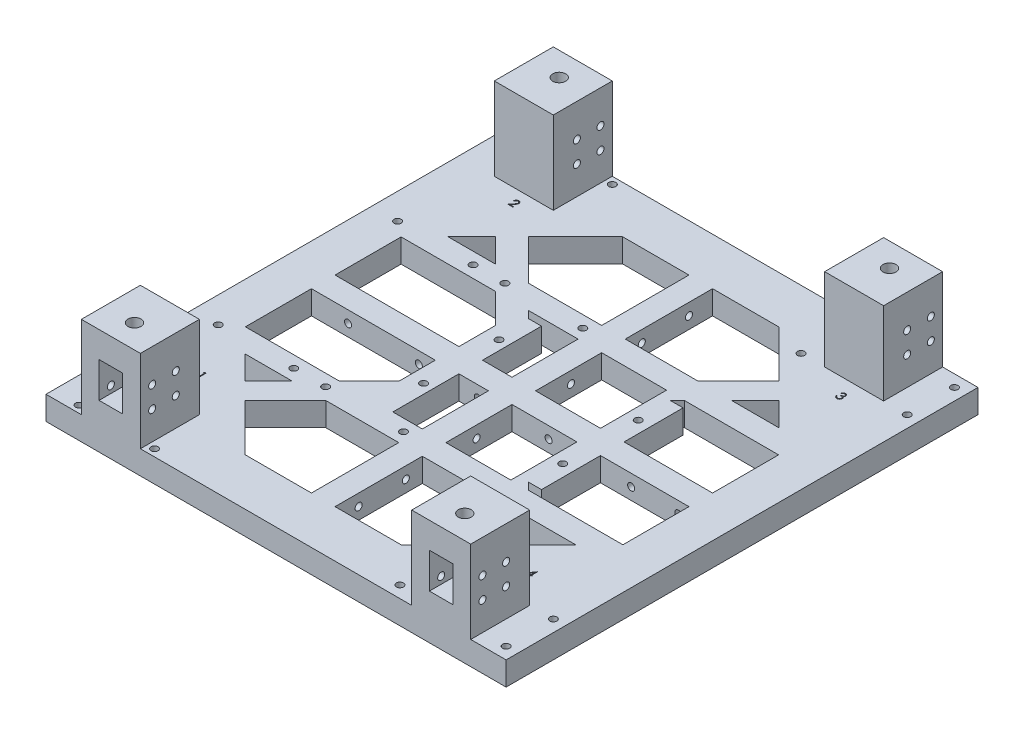
SolidWorks part; units mm, degrees
ref_plane "前视基准面" through (0, 0, 0) normal (0, 0, 1) x (1, 0, 0)
ref_plane "上视基准面" through (0, 0, 0) normal (0, 1, 0) x (1, 0, 0)
ref_plane "右视基准面" through (0, 0, 0) normal (1, 0, 0) x (0, 0, -1)
sketch "草图1" plane through (0, 0, 0) normal (0, 1, 0) x (1, 0, 0)
  line L1 (-97.5, -100) -> (97.5, -100)
  line L2 (-97.5, -100) -> (-97.5, 100)
  line L3 (-97.5, 100) -> (97.5, 100)
  line L4 (97.5, -100) -> (97.5, 100)
  line L5 (-97.5, -100) -> (97.5, 100) construction
  line L6 (-97.5, 100) -> (97.5, -100) construction
  point P0 (0, 0)
  dimension "D1" = 195
  dimension "D2" = 200
extrude "凸台-拉伸1" add sketch "草图1" along normal blind 10
sketch "草图2" plane through (0, 10, 0) normal (0, 1, 0) x (1, 0, 0)
  line L1 (-82.5, -100) -> (-57.5, -100)
  line L2 (-82.5, -100) -> (-82.5, -75)
  line L3 (-82.5, -75) -> (-57.5, -75)
  line L4 (-57.5, -100) -> (-57.5, -75)
  line L6 (-82.5, 100) -> (-57.5, 100)
  line L7 (-82.5, 100) -> (-82.5, 75)
  line L8 (-82.5, 75) -> (-57.5, 75)
  line L9 (-57.5, 100) -> (-57.5, 75)
  line L10 (82.5, 100) -> (57.5, 100)
  line L11 (82.5, 100) -> (82.5, 75)
  line L12 (82.5, 75) -> (57.5, 75)
  line L13 (57.5, 100) -> (57.5, 75)
  line L14 (97.5, 100) -> (-97.5, 100) construction
  line L15 (82.5, -75) -> (57.5, -75)
  line L16 (82.5, -75) -> (82.5, -100)
  line L17 (82.5, -100) -> (57.5, -100)
  line L18 (57.5, -75) -> (57.5, -100)
  line L19 (-97.5, -100) -> (97.5, -100) construction
  line L22 (97.5, -100) -> (97.5, 100) construction
  line L23 (-97.5, 100) -> (-97.5, -100) construction
  dimension "D1" = 0
  dimension "D2" = 0
  dimension "D3" = 0
  dimension "D4" = 0
  dimension "D5" = 40
  dimension "D6" = 25
  dimension "D7" = 40
  dimension "D8" = 25
  dimension "D9" = 25
  dimension "D10" = 25
  dimension "D11" = 25
  dimension "D12" = 25
  dimension "D13" = 40
  dimension "D14" = 25
  dimension "D15" = 40
  dimension "D16" = 25
extrude "凸台-拉伸2" add sketch "草图2" along normal blind 35
sketch "草图3" plane through (0, 0, 100) normal (0, 0, 1) x (1, 0, 0)
  line L0 (57.5, 45) -> (82.5, 45) construction
  line L1 (65, 19) -> (75, 19)
  line L2 (65, 19) -> (65, 34)
  line L3 (65, 34) -> (75, 34)
  line L4 (75, 19) -> (75, 34)
  line L5 (82.5, 45) -> (82.5, 10) construction
  dimension "D1" = 10
  dimension "D2" = 11
  dimension "D3" = 7.5
  dimension "D4" = 15
extrude "切除-拉伸1" cut sketch "草图3" against normal blind 20
sketch "草图4" plane through (0, 0, 0) normal (1, 0, 0) x (0, 0, -1)
  line L0 (0, 44.1564) -> (0, 0) construction
mirror "镜向1" about plane through (0, 0, 0) normal (1, 0, 0) of "切除-拉伸1"
mirror "镜向2" about plane through (0, 0, 0) normal (0, 0, 1) of "镜向1", "切除-拉伸1"
sketch "草图6" plane through (65, 0, 0) normal (1, 0, 0) x (0, 0, -1)
  line L0 (-80, 34) -> (-80, 19) construction
  line L1 (-95, 22) -> (-85, 22)
  line L2 (-95, 22) -> (-95, 31)
  line L3 (-95, 31) -> (-85, 31)
  line L4 (-85, 22) -> (-85, 31)
  line L5 (-80, 34) -> (-100, 34) construction
  line L6 (-80, 19) -> (-100, 19) construction
  circle A0 centre (-85, 31) radius 1.5
  circle A1 centre (-85, 22) radius 1.5
  circle A2 centre (-95, 22) radius 1.5
  circle A3 centre (-95, 31) radius 1.5
  dimension "D5" = 3
  dimension "D6" = 3
  dimension "D7" = 3
  dimension "D8" = 3
  dimension "D1" = 5
  dimension "D2" = 3
  dimension "D3" = 3
  dimension "D4" = 10
extrude "切除-拉伸2" cut sketch "草图6" against normal through all and the other way through all contours L3 A3 L2 | L2 A3 L3 | L3 A0 L4 | L4 A0 L3 | L1 A1 L4 | L2 A2 L1 | L1 A2 L2 | L4 A1 L1
mirror "镜向3" about plane through (0, 0, 0) normal (0, 0, 1) of "切除-拉伸2"
sketch "草图7" plane through (0, 0, 0) normal (0, -1, 0) x (1, 0, 0)
  line L0 (97.5, 100) -> (97.5, -100) construction
  line L1 (97.5, -100) -> (-97.5, -100) construction
  circle A0 centre (92.5, -75) radius 1.5
  circle A1 centre (92.5, -95) radius 1.5
  circle A2 centre (47.5, -75) radius 1.5
  circle A3 centre (47.5, -95) radius 1.5
  dimension "D1" = 3
  dimension "D2" = 3
  dimension "D3" = 3
  dimension "D4" = 3
  dimension "D5" = 5
  dimension "D6" = 5
  dimension "D7" = 5
  dimension "D8" = 5
  dimension "D9" = 20
  dimension "D10" = 45
  dimension "D11" = 45
  dimension "20" = 20
extrude "切除-拉伸3" cut sketch "草图7" against normal through all
mirror "镜向4" about plane through (0, 0, 0) normal (0, 0, 1) of "切除-拉伸3"
sketch "草图9" plane through (0, 45, 0) normal (0, 1, 0) x (1, 0, 0)
  line L0 (-82.5, 100) -> (-82.5, 75) construction
  line L1 (-57.5, 100) -> (-82.5, 100) construction
  circle A0 centre (-70, 90) radius 1.5
  dimension "D1" = 3
  dimension "D2" = 12.5
  dimension "D3" = 10
extrude "切除-拉伸4" cut sketch "草图9" against normal through all
sketch "草图10" plane through (0, 45, 0) normal (0, 1, 0) x (1, 0, 0)
  circle A0 centre (-70, 90) radius 2.75
  dimension "D1" = 5.5
extrude "切除-拉伸5" cut sketch "草图10" against normal blind 4
sketch "草图11" plane through (0, 0, 0) normal (0, -1, 0) x (-1, 0, 0)
  line L1 (70, 86.8246) -> (72.75, 88.4123)
  line L2 (72.75, 88.4123) -> (72.75, 91.5877)
  line L3 (72.75, 91.5877) -> (70, 93.1754)
  line L4 (70, 93.1754) -> (67.25, 91.5877)
  line L5 (67.25, 91.5877) -> (67.25, 88.4123)
  line L6 (67.25, 88.4123) -> (70, 86.8246)
  circle A0 centre (70, 90) radius 2.75 construction
  dimension "D1" = 5.5
extrude "切除-拉伸6" cut sketch "草图11" against normal blind 8
sketch "草图13" plane through (0, 0, 0) normal (0, -1, 0) x (-1, 0, 0)
  line L0 (-97.5, 100) -> (97.5, 100) construction
  line L1 (86.5, 38) -> (54.5, 38)
  line L2 (86.5, 38) -> (86.5, 97)
  line L3 (86.5, 97) -> (54.5, 97)
  line L4 (54.5, 38) -> (54.5, 97)
  line L5 (97.5, 100) -> (97.5, -100) construction
  circle A0 centre (86.5, 38) radius 1.5
  circle A1 centre (54.5, 38) radius 1.5
  circle A2 centre (54.5, 97) radius 1.5
  circle A3 centre (86.5, 97) radius 1.5
  dimension "D4" = 3
  dimension "D5" = 3
  dimension "D6" = 3
  dimension "D7" = 3
  dimension "D1" = 3
  dimension "D2" = 59
  dimension "D3" = 32
  dimension "D8" = 11
extrude "切除-拉伸7" cut sketch "草图13" against normal through all contours A0 | A1 | A2 | A3
mirror "镜向5" about plane through (0, 0, 0) normal (0, 0, 1) of "切除-拉伸7"
sketch "草图14" plane through (0, 0, 0) normal (0, -1, 0) x (-1, 0, 0)
  circle A0 centre (41, 38) radius 1.5
  circle A1 centre (41, -38) radius 1.5
  circle A2 centre (54.5, 38) radius 1.5 construction
  circle A3 centre (54.5, -38) radius 1.5 construction
  dimension "D1" = 3
  dimension "D2" = 3
  dimension "D3" = 13.5
  dimension "D4" = 13.5
  dimension "D5" = 0
  dimension "D6" = 0
extrude "切除-拉伸8" cut sketch "草图14" against normal blind 10
pattern_linear "阵列(线性)1" count 2 spacing 33 along (1, 0, 0) of "切除-拉伸8"
sketch "草图19" plane through (0, 10, 0) normal (0, 1, 0) x (1, 0, 0)
  line L0 (57.5, 100) -> (-57.5, 100) construction
  line L1 (33.1371, 80) -> (-33.1371, 80)
  line L2 (-33.1371, 80) -> (-80, 33.1371)
  line L3 (-80, 33.1371) -> (-80, -33.1371)
  line L4 (-80, -33.1371) -> (-33.1371, -80)
  line L5 (-33.1371, -80) -> (33.1371, -80)
  line L6 (33.1371, -80) -> (80, -33.1371)
  line L7 (80, -33.1371) -> (80, 33.1371)
  line L8 (80, 33.1371) -> (33.1371, 80)
  line L9 (-54.5, 38) -> (-54.5, 43)
  line L10 (-54.5, 43) -> (-54.5, 33)
  line L11 (-54.5, 33) -> (-80, 33)
  line L12 (-54.5, 43) -> (-70.1371, 43)
  line L13 (-54.5, 43) -> (70.1371, 43)
  line L14 (-54.5, 33) -> (80, 33)
  line L16 (-84.7159, -33) -> (86.4481, -33)
  line L17 (-84.7159, -33) -> (-84.7159, -43)
  line L18 (-84.7159, -43) -> (86.4481, -43)
  line L19 (86.4481, -33) -> (86.4481, -43)
  circle A0 centre (0, 0) radius 80 construction
  dimension "D1" = 20
  dimension "D2" = 5
  dimension "D3" = 10
  dimension "D4" = 10
  dimension "D5" = 5
extrude "切除-拉伸9" cut sketch "草图19" against normal blind 10 contours L12 L13 L8 L1 L2 | L3 L16 L7 L14 L11 | L18 L4 L5 L6
sketch "草图20" plane through (0, 0, 0) normal (0, -1, 0) x (1, 0, 0)
  line L0 (33.1371, 80) -> (-33.1371, 80) construction
  line L1 (-5, -80) -> (5, -80)
  line L2 (-5, -80) -> (-5, 80)
  line L3 (-5, 80) -> (5, 80)
  line L4 (5, -80) -> (5, 80)
  line L5 (-5, -80) -> (5, 80) construction
  line L6 (-5, 80) -> (5, -80) construction
  point P0 (0, 0)
  dimension "D1" = 10
extrude "凸台-拉伸8" add sketch "草图20" against normal blind 10
pattern_circular "阵列(圆周)1" count 5 every 45 about axis through (0, 0, 0) along (0, 1, 0) of "凸台-拉伸8"
sketch "草图22" plane through (0, 0, 0) normal (0, -1, 0) x (1, 0, 0)
  circle A0 centre (-41, 38) radius 1.5
  circle A1 centre (-41, -38) radius 1.5
  dimension "D1" = 0
  dimension "D2" = 0
extrude "切除-拉伸10" cut sketch "草图22" against normal blind 10
sketch "草图23" plane through (0, 0, 0) normal (0, -1, 0) x (-1, 0, 0)
  line L0 (25.9289, -33) -> (5, -33) construction
  line L1 (27.5, 30) -> (17.5, 30)
  line L2 (27.5, 30) -> (27.5, -33)
  line L3 (27.5, -33) -> (17.5, -33)
  line L4 (17.5, 30) -> (17.5, -33)
  line L5 (27.5, 30) -> (17.5, -33) construction
  line L6 (27.5, -33) -> (17.5, 30) construction
  line L7 (97.5, 100) -> (97.5, -100) construction
  line L9 (-32.5, 30) -> (-42.5, 30)
  line L10 (-32.5, 30) -> (-32.5, -30)
  line L11 (-32.5, -30) -> (-42.5, -30)
  line L12 (-42.5, 30) -> (-42.5, -30)
  line L13 (-32.5, 30) -> (-42.5, -30) construction
  line L14 (-32.5, -30) -> (-42.5, 30) construction
  point P0 (22.5, -1.5)
  point P9 (-37.5, 0)
  dimension "D1" = 10
  dimension "D2" = 70
  dimension "D3" = 10
  dimension "D4" = 130
extrude "凸台-拉伸10" add sketch "草图23" against normal blind 10
mirror "镜向6" about plane through (0, 0, 0) normal (0, 0, 1) of "切除-拉伸6", "切除-拉伸4", "切除-拉伸5"
mirror "镜向7" about plane through (0, 0, 0) normal (1, 0, 0) of "镜向6", "切除-拉伸4", "切除-拉伸5", "切除-拉伸6"
sketch "草图24" plane through (0, 10, 0) normal (0, 1, 0) x (1, 0, 0)
  line L0 (57.5, 100) -> (-57.5, 100) construction
  line L1 (-27.5, 5) -> (-27.5, 20.4289) construction
  line L2 (-27.5, -20.4289) -> (-27.5, -5) construction
  line L3 (32.5, 5) -> (32.5, 25.4289) construction
  line L4 (32.5, -25.4289) -> (32.5, -5) construction
  circle A0 centre (-21.5, 16) radius 1.5
  circle A1 centre (-21.5, -16) radius 1.5
  circle A2 centre (37.5, 16) radius 1.5
  circle A3 centre (37.5, -16) radius 1.5
  dimension "D1" = 3
  dimension "D2" = 3
  dimension "D3" = 84
  dimension "D5" = 6
  dimension "D6" = 6
  dimension "D7" = 3
  dimension "D8" = 3
  dimension "D9" = 5
  dimension "D10" = 5
  dimension "D4" = 116
extrude "切除-拉伸11" cut sketch "草图24" against normal through all
sketch "草图25" plane through (0, 10, 0) normal (0, 1, 0) x (1, 0, 0)
  line L1 (5, 33) -> (32.5, 33)
  line L2 (5, 33) -> (5, 5)
  line L3 (5, 5) -> (32.5, 5)
  line L4 (32.5, 33) -> (32.5, 5)
  line L5 (32.5, -5) -> (5, -5)
  line L6 (32.5, -5) -> (32.5, -33)
  line L7 (32.5, -33) -> (5, -33)
  line L8 (5, -5) -> (5, -33)
  line L9 (-5, -33) -> (-17.5, -33)
  line L10 (-5, -33) -> (-5, -5)
  line L11 (-5, -5) -> (-17.5, -5)
  line L12 (-17.5, -33) -> (-17.5, -5)
  line L13 (-17.5, 5) -> (-5, 5)
  line L14 (-17.5, 5) -> (-17.5, 33)
  line L15 (-17.5, 33) -> (-5, 33)
  line L16 (-5, 5) -> (-5, 33)
extrude "切除-拉伸12" cut sketch "草图25" against normal through all
sketch "草图26" plane through (0, 0, 5) normal (0, 0, 1) x (1, 0, 0)
  line L0 (97.5, 10) -> (97.5, 0) construction
  line L1 (-97.5, 0) -> (97.5, 0) construction
  circle A0 centre (75.5, 5) radius 1.5
  dimension "D1" = 3
  dimension "D2" = 22
  dimension "D3" = 5
extrude "切除-拉伸13" cut sketch "草图26" against normal blind 10
pattern_linear "阵列(线性)2" count 2 spacing 20 along (-1, 0, 0) of "切除-拉伸13"
pattern_linear "阵列(线性)3" count 2 spacing 55 along (-1, 0, 0) of "切除-拉伸13"
pattern_linear "阵列(线性)4" count 2 spacing 85 along (-1, 0, 0) of "阵列(线性)3", "切除-拉伸13"
pattern_linear "阵列(线性)5" count 2 spacing 110 along (-1, 0, 0) of "切除-拉伸13"
sketch "草图27" plane through (5, 0, 0) normal (1, 0, 0) x (0, 0, -1)
  line L0 (-100, 10) -> (100, 10) construction
  line L1 (100, 10) -> (100, 0) construction
  circle A0 centre (70, 5) radius 1.5
  dimension "D1" = 3
  dimension "D2" = 5
  dimension "D3" = 30
extrude "切除-拉伸14" cut sketch "草图27" against normal blind 10
pattern_linear "阵列(线性)6" count 2 spacing 20 along (0, 0, 1) of "切除-拉伸14"
pattern_linear "阵列(线性)7" count 2 spacing 50 along (0, 0, 1) of "切除-拉伸14"
mirror "镜向8" about plane through (0, 0, 0) normal (0, 0, 1) of "阵列(线性)7", "切除-拉伸14"
mirror "镜向9" about plane through (0, 0, 0) normal (0, 0, 1) of "阵列(线性)6"
sketch "草图28" plane through (0, 10, 0) normal (0, 1, 0) x (1, 0, 0)
  text T0 "1"
extrude "切除-拉伸15" cut sketch "草图28" against normal blind 3
sketch "草图29" plane through (0, 10, 0) normal (0, 1, 0) x (1, 0, 0)
  text T0 "2"
extrude "切除-拉伸16" cut sketch "草图29" against normal blind 3
sketch "草图30" plane through (0, 10, 0) normal (0, 1, 0) x (1, 0, 0)
  text T0 "3"
extrude "切除-拉伸17" cut sketch "草图30" against normal blind 3
sketch "草图31" plane through (0, 10, 0) normal (0, 1, 0) x (1, 0, 0)
  text T0 "4"
extrude "切除-拉伸18" cut sketch "草图31" against normal blind 3
